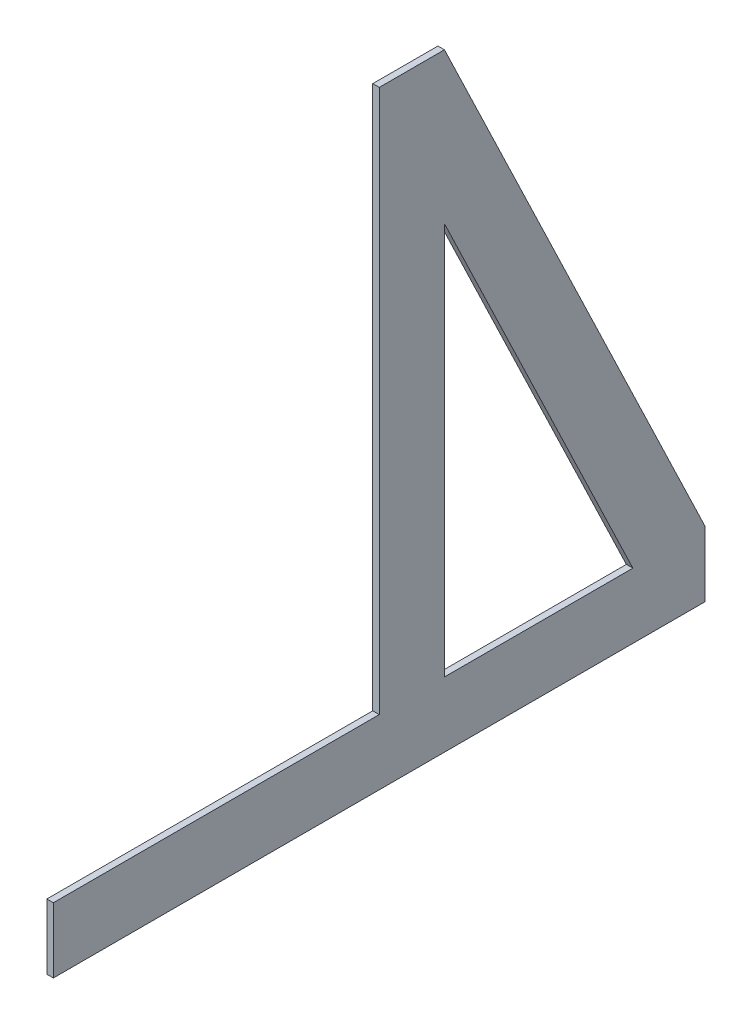
SolidWorks part; units mm, degrees
material "Клен"
ref_plane "Спереди" through (0, 0, 0) normal (0, 0, 1) x (1, 0, 0)
ref_plane "Сверху" through (0, 0, 0) normal (0, 1, 0) x (1, 0, 0)
ref_plane "Справа" through (0, 0, 0) normal (1, 0, 0) x (0, 0, -1)
sketch "боковина" plane through (0, 0, 0) normal (1, 0, 0) x (0, 0, -1)
  line L0 (-593.8462, -224.4615) -> (6.1538, -224.4615)
  line L1 (6.1538, -224.4615) -> (6.1538, -164.4615)
  line L2 (6.1538, -164.4615) -> (-233.8462, 335.5385)
  line L3 (-233.8462, 335.5385) -> (-293.8462, 335.5385)
  line L4 (-293.8462, 335.5385) -> (-293.8462, -164.4615)
  line L5 (-293.8462, -164.4615) -> (-593.8462, -164.4615)
  line L6 (-593.8462, -164.4615) -> (-593.8462, -224.4615)
  line L7 (-233.8462, -164.4615) -> (-60.4002, -164.4615)
  line L8 (-60.4002, -164.4615) -> (-233.8462, 196.8842)
  line L9 (-233.8462, 196.8842) -> (-233.8462, -164.4615)
  dimension "D1" = 60
  dimension "D2" = 60
  dimension "D3" = 600
  dimension "D5" = 60
  dimension "D6" = 300
  dimension "D7" = 60
  dimension "D8" = 60
  dimension "D4" = 500
extrude "Бобышка-боковина" add sketch "боковина" along normal blind 6
equation "\"D2@боковина\" = \"D1@боковина\""
equation "\"D5@боковина\" = \"D1@боковина\""
equation "\"D7@боковина\" = \"D1@боковина\""
equation "\"D8@боковина\" = \"D1@боковина\""
